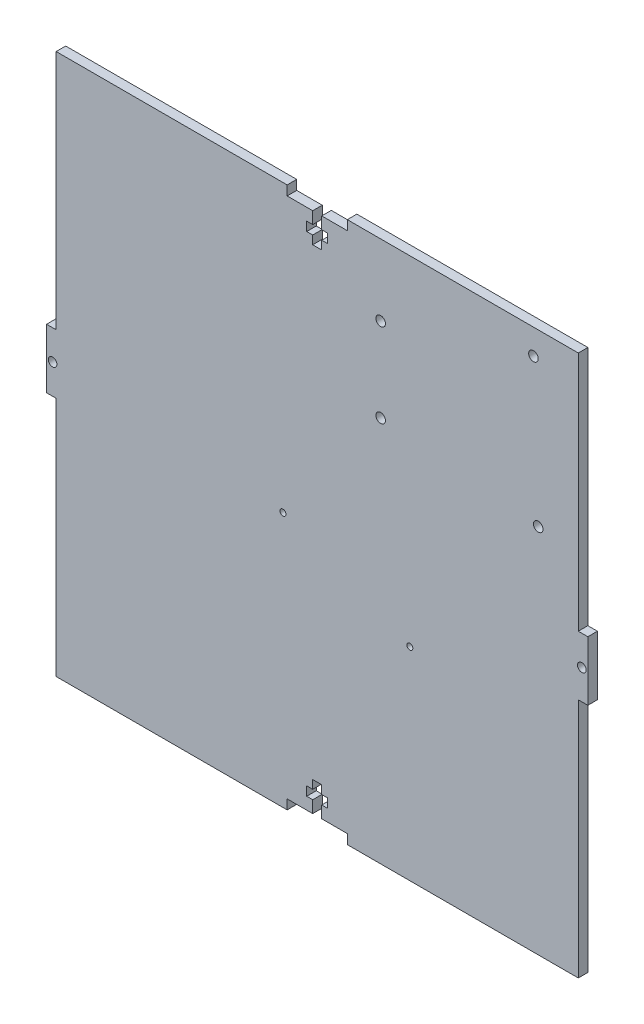
SolidWorks part; units mm, degrees
ref_plane "Front Plane" through (0, 0, 0) normal (0, 0, 1) x (1, 0, 0)
ref_plane "Top Plane" through (0, 0, 0) normal (0, 1, 0) x (1, 0, 0)
ref_plane "Right Plane" through (0, 0, 0) normal (1, 0, 0) x (0, 0, -1)
sketch "Sketch3" plane through (0, 0, 0) normal (0, 0, 1) x (1, 0, 0)
  line L0 (-90, 0) -> (90, 0) construction
  line L1 (-90, 90) -> (90, 90)
  line L2 (-90, 90) -> (-90, -90)
  line L3 (-90, -90) -> (90, -90)
  line L4 (90, 90) -> (90, -90)
  line L5 (-90, 0) -> (42.6717, 0) construction
  line L6 (0, 42.4898) -> (0, -90) construction
  circle A0 centre (-11.3989, -5.0756) radius 1
  circle A1 centre (30.8011, -22.5756) radius 1
  circle A2 centre (73.5, 33.3417) radius 1.59
  circle A3 centre (21.1, 38.4417) radius 1.59
  circle A4 centre (21.1, 66.3417) radius 1.59
  circle A5 centre (71.9, 81.6417) radius 1.59
  dimension "D2" = 3.18
  dimension "D4" = 3.18
  dimension "D5" = 3.18
  dimension "D6" = 3.18
  dimension "D7" = 2
  dimension "D8" = 2
  dimension "D1" = 180
  dimension "D3" = 180
extrude "Boss-Extrude1" add sketch "Sketch3" along normal blind 3.18
sketch "Sketch4" plane through (0, 0, 3.18) normal (0, 0, 1) x (1, 0, 0)
  line L0 (-90, 90) -> (-90, -90) construction
  line L1 (90, -90) -> (90, 90) construction
  line L2 (-90, 0) -> (90, 0) construction
  line L3 (0.9399, -90) -> (0, -90) construction
  line L4 (90, 90) -> (-90, 90) construction
  line L5 (0, -90) -> (0, 90) construction
  line L6 (1.5, 86.82) -> (10, 86.82)
  line L7 (-10, 90) -> (10, 90)
  line L8 (-10, 90) -> (-10, 86.82)
  line L9 (-10, 86.82) -> (-1.5, 86.82)
  line L10 (10, 90) -> (10, 86.82)
  line L11 (-3.5, 82.82) -> (-1.5, 82.82)
  line L12 (-3.5, 82.82) -> (-3.5, 79.82)
  line L13 (-3.5, 79.82) -> (-1.5, 79.82)
  line L14 (3.5, 82.82) -> (3.5, 79.82)
  line L15 (1.5, 82.82) -> (3.5, 82.82)
  line L16 (-1.5, 86.82) -> (-1.5, 82.82)
  line L17 (-1.5, 77) -> (1.5, 77)
  line L18 (1.5, 86.82) -> (1.5, 82.82)
  line L19 (-90, -90) -> (90, -90) construction
  line L20 (1.5, 79.82) -> (3.5, 79.82)
  line L21 (-1.5, 79.82) -> (-1.5, 77)
  line L22 (1.5, 79.82) -> (1.5, 77)
  line L23 (1.5, -79.82) -> (1.5, -77)
  line L24 (-1.5, -79.82) -> (-1.5, -77)
  line L25 (1.5, -79.82) -> (3.5, -79.82)
  line L26 (1.5, -86.82) -> (1.5, -82.82)
  line L27 (-1.5, -77) -> (1.5, -77)
  line L28 (-1.5, -86.82) -> (-1.5, -82.82)
  line L29 (1.5, -82.82) -> (3.5, -82.82)
  line L30 (3.5, -82.82) -> (3.5, -79.82)
  line L31 (-3.5, -79.82) -> (-1.5, -79.82)
  line L32 (-3.5, -82.82) -> (-3.5, -79.82)
  line L33 (-3.5, -82.82) -> (-1.5, -82.82)
  line L34 (10, -90) -> (10, -86.82)
  line L35 (-10, -86.82) -> (-1.5, -86.82)
  line L36 (-10, -90) -> (-10, -86.82)
  line L37 (-10, -90) -> (10, -90)
  line L38 (1.5, -86.82) -> (10, -86.82)
  dimension "D1" = 20
  dimension "D2" = 3.18
  dimension "D3" = 4
  dimension "D4" = 3
  dimension "D5" = 3
  dimension "D6" = 13
  dimension "D7" = 7
sketch "Sketch5" plane through (0, 0, 3.18) normal (0, 0, 1) x (1, 0, 0)
  line L0 (-90, 0) -> (90, 0) construction
  line L1 (-90, 90) -> (-86.82, 90)
  line L2 (-90, 90) -> (-90, 9.875)
  line L3 (-90, 9.875) -> (-86.82, 9.875)
  line L4 (-86.82, 90) -> (-86.82, 9.875)
  line L5 (-90, -90) -> (-86.82, -90)
  line L6 (-90, -90) -> (-90, -9.875)
  line L7 (-90, -9.875) -> (-86.82, -9.875)
  line L8 (-86.82, -90) -> (-86.82, -9.875)
  line L9 (-90, 90) -> (-90, -90) construction
  line L10 (0, 90) -> (0, -90) construction
  line L11 (86.82, -90) -> (86.82, -9.875)
  line L12 (90, -9.875) -> (86.82, -9.875)
  line L13 (90, -90) -> (90, -9.875)
  line L14 (90, -90) -> (86.82, -90)
  line L15 (86.82, 90) -> (86.82, 9.875)
  line L16 (90, 9.875) -> (86.82, 9.875)
  line L17 (90, 90) -> (90, 9.875)
  line L18 (90, 90) -> (86.82, 90)
  circle A0 centre (-88, 0) radius 1.436
  circle A1 centre (88, 0) radius 1.436
  dimension "D4" = 2.872
  dimension "D5" = 2
  dimension "D1" = 3.18
  dimension "D2" = 3.18
  dimension "D3" = 19.75
extrude "Cut-Extrude1" cut sketch "Sketch4" against normal through all
extrude "Cut-Extrude2" cut sketch "Sketch5" against normal through all
